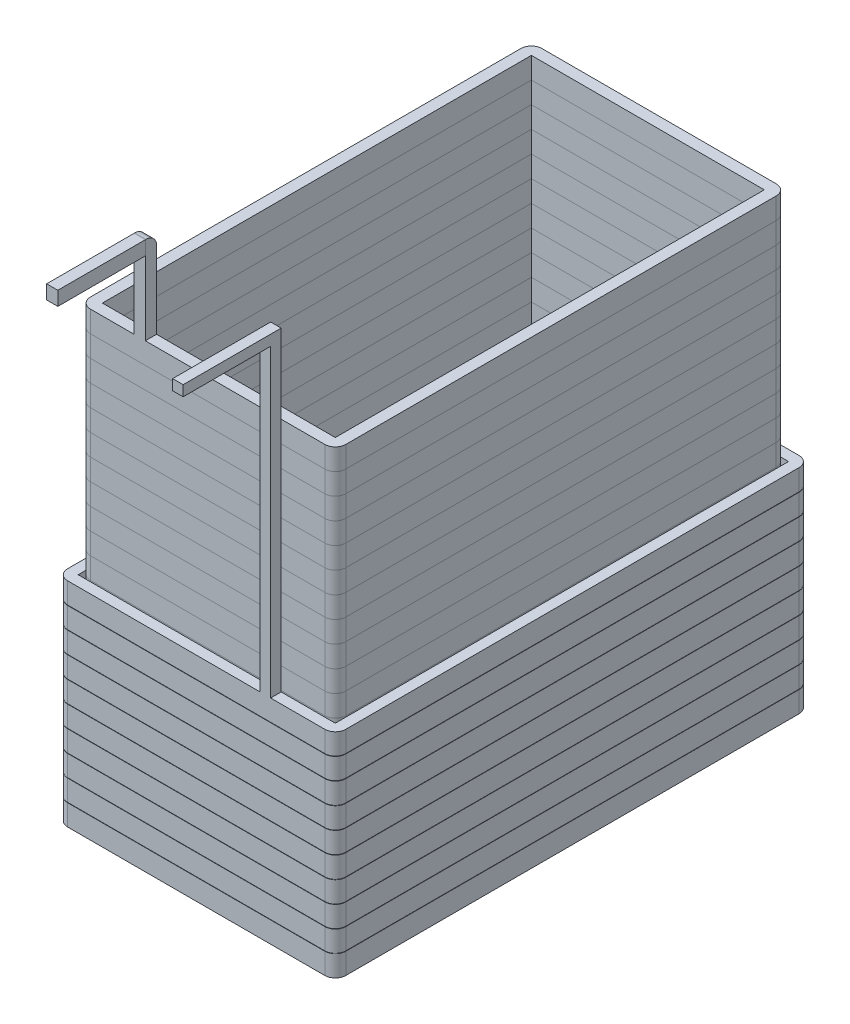
SolidWorks part; units mm, degrees
ref_plane "Front Plane" through (0, 0, 0) normal (0, 0, 1) x (1, 0, 0)
ref_plane "Top Plane" through (0, 0, 0) normal (0, 1, 0) x (1, 0, 0)
ref_plane "Right Plane" through (0, 0, 0) normal (1, 0, 0) x (0, 0, -1)
sketch "Sketch1" plane through (0, 0, 0) normal (0, 1, 0) x (1, 0, 0)
  line L0 (33.26, 61.26) -> (-33.26, 61.26)
  line L1 (33, -61) -> (-33, -61)
  line L2 (33, -61) -> (33, 61)
  line L3 (33, 61) -> (-33, 61)
  line L4 (-33, -61) -> (-33, 61)
  line L5 (33, -61) -> (-33, 61) construction
  line L6 (33, 61) -> (-33, -61) construction
  line L7 (-33.26, -61.26) -> (-33.26, 61.26)
  line L8 (33.26, -61.26) -> (-33.26, -61.26)
  line L9 (33.26, -61.26) -> (33.26, 61.26)
  line L10 (33.46, 64.46) -> (-33.46, 64.46)
  line L11 (-36.46, -61.46) -> (-36.46, 61.46)
  line L12 (33.46, -64.46) -> (-33.46, -64.46)
  line L13 (36.46, -61.46) -> (36.46, 61.46)
  line L14 (36.46, -64.46) -> (-36.46, -64.46) construction
  line L15 (36.46, -64.46) -> (36.46, 64.46) construction
  line L16 (-36.46, -64.46) -> (-36.46, 64.46) construction
  line L17 (36.46, 64.46) -> (-36.46, 64.46) construction
  arc A0 (33.46, -64.46) -> (36.46, -61.46) centre (33.46, -61.46) ccw
  arc A1 (-33.46, -64.46) -> (-36.46, -61.46) centre (-33.46, -61.46) cw
  arc A2 (36.46, 61.46) -> (33.46, 64.46) centre (33.46, 61.46) ccw
  arc A3 (-36.46, 61.46) -> (-33.46, 64.46) centre (-33.46, 61.46) cw
  point P0 (0, 0)
  dimension "D5" = 3
  dimension "D6" = 3
  dimension "D7" = 3
  dimension "D8" = 3
  dimension "D1" = 122
  dimension "D2" = 66
  dimension "D3" = 0.26
  dimension "D4" = 3.2
extrude "Boss-Extrude2" add sketch "Sketch1" along normal blind 6.1 contours L12 L13 L10 L11 L9 L8 L7 L0
pattern_linear "LPattern2" count 21 spacing 6.1 along (0, 1, 0) of "Boss-Extrude2"
sketch "Sketch2" plane through (0, 128.1, 0) normal (0, 1, 0) x (1, 0, 0)
  line L1 (-20.9836, -61.26) -> (-17.7941, -61.26)
  line L2 (-20.9836, -61.26) -> (-20.9836, -64.46)
  line L3 (-20.9836, -64.46) -> (-17.7941, -64.46)
  line L4 (-17.7941, -61.26) -> (-17.7941, -64.46)
  line L6 (-36.46, -61.46) -> (-36.46, 61.46) construction
  dimension "D1" = 15.4764
  dimension "D2" = 3.1895
  dimension "D3" = 3.2
extrude "Boss-Extrude3" add sketch "Sketch2" along normal blind 25
sketch "Sketch3" plane through (0, 0, 64.46) normal (0, 0, 1) x (1, 0, 0)
  line L0 (-17.7941, 153.1) -> (-17.7941, 128.1) construction
  line L4 (-17.7941, 153.1) -> (-17.7941, 149.1)
  line L6 (-20.9836, 149.1) -> (-20.9836, 153.1)
  line L7 (-20.9836, 153.1) -> (-20.9836, 128.1) construction
  line L8 (-20.9836, 153.1) -> (-17.7941, 153.1)
  line L9 (-20.9836, 149.1) -> (-17.7941, 149.1)
  dimension "D1" = 4
extrude "Boss-Extrude4" add sketch "Sketch3" along normal blind 25
fillet "Fillet1" radius 3 1 edges at (-19.3889, 153.1, 61.26)
sketch "Sketch4" plane through (0, 0, 0) normal (0, -1, 0) x (-1, 0, 0)
  line L0 (-33.46, -64.46) -> (33.46, -64.46) construction
  line L1 (-36.72, 64.72) -> (36.72, 64.72)
  line L2 (-36.72, 64.72) -> (-36.72, -64.72)
  line L3 (-36.72, -64.72) -> (36.72, -64.72)
  line L4 (36.72, 64.72) -> (36.72, -64.72)
  line L5 (-36.72, 64.72) -> (36.72, -64.72) construction
  line L6 (-36.72, -64.72) -> (36.72, 64.72) construction
  line L7 (36.46, -61.46) -> (36.46, 61.46) construction
  line L8 (-36.72, -67.72) -> (36.72, -67.72)
  line L9 (39.72, 64.72) -> (39.72, -64.72)
  line L10 (-36.72, 67.72) -> (36.72, 67.72)
  line L11 (-39.72, 64.72) -> (-39.72, -64.72)
  line L12 (-39.72, 67.72) -> (39.72, 67.72) construction
  line L13 (-39.72, 67.72) -> (-39.72, -67.72) construction
  line L14 (39.72, 67.72) -> (39.72, -67.72) construction
  line L15 (-39.72, -67.72) -> (39.72, -67.72) construction
  arc A0 (-36.72, 67.72) -> (-39.72, 64.72) centre (-36.72, 64.72) ccw
  arc A1 (39.72, 64.72) -> (36.72, 67.72) centre (36.72, 64.72) ccw
  arc A2 (-36.72, -67.72) -> (-39.72, -64.72) centre (-36.72, -64.72) cw
  arc A3 (36.72, -67.72) -> (39.72, -64.72) centre (36.72, -64.72) ccw
  point P0 (0, 0)
  dimension "D4" = 3
  dimension "D1" = 0.26
  dimension "D2" = 0.26
  dimension "D3" = 3
extrude "Boss-Extrude5" add sketch "Sketch4" against normal blind 6 separate body
pattern_linear "LPattern3" count 10 spacing 6.1 along (0, 1, 0) of bodies 128
sketch "Sketch5" plane through (0, 60.9, 0) normal (0, 1, 0) x (1, 0, 0)
  line L0 (36.72, -64.72) -> (-36.72, -64.72) construction
  line L1 (18.26, -64.72) -> (21.26, -64.72)
  line L2 (18.26, -64.72) -> (18.26, -67.72)
  line L3 (18.26, -67.72) -> (21.26, -67.72)
  line L4 (21.26, -64.72) -> (21.26, -67.72)
  line L5 (36.72, -67.72) -> (-36.72, -67.72) construction
  line L6 (33.26, -61.26) -> (33.26, 61.26) construction
  dimension "D1" = 3
  dimension "D2" = 12
extrude "Boss-Extrude6" add sketch "Sketch5" along normal blind 90
sketch "Sketch6" plane through (0, 0, 67.72) normal (0, 0, 1) x (1, 0, 0)
  line L0 (21.26, 150.9) -> (21.26, 60.9) construction
  line L1 (18.26, 150.9) -> (21.26, 150.9)
  line L2 (18.26, 150.9) -> (18.26, 147.9)
  line L3 (18.26, 147.9) -> (21.26, 147.9)
  line L4 (21.26, 150.9) -> (21.26, 147.9)
  dimension "D1" = 3
extrude "Boss-Extrude7" add sketch "Sketch6" along normal blind 25
